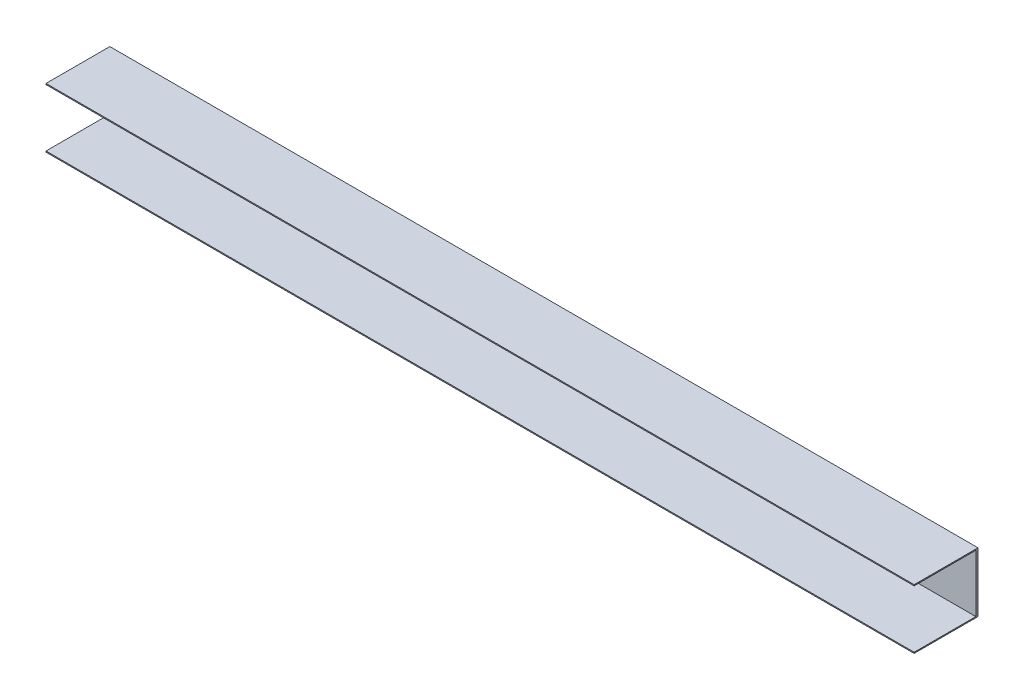
SolidWorks part; units mm, degrees
material "1060 Alloy"
ref_plane "Front Plane" through (0, 0, 0) normal (0, 0, 1) x (1, 0, 0)
ref_plane "Top Plane" through (0, 0, 0) normal (0, 1, 0) x (1, 0, 0)
ref_plane "Right Plane" through (0, 0, 0) normal (1, 0, 0) x (0, 0, -1)
sketch "Sketch1" plane through (0, 0, 0) normal (0, 0, 1) x (1, 0, 0)
  line L1 (-204, 14) -> (204, 14)
  line L2 (-204, 14) -> (-204, -14)
  line L3 (-204, -14) -> (204, -14)
  line L4 (204, 14) -> (204, -14)
  line L5 (-204, 14) -> (204, -14) construction
  line L6 (-204, -14) -> (204, 14) construction
  point P0 (0, 0)
  dimension "D1" = 28
  dimension "D2" = 408
extrude "Boss-Extrude1" add sketch "Sketch1" along normal blind 30
sketch "Sketch2" plane through (0, 0, 30) normal (0, 0, 1) x (1, 0, 0)
  line L1 (213.5, -13.5) -> (-213.5, -13.5)
  line L2 (213.5, -13.5) -> (213.5, 13.5)
  line L3 (213.5, 13.5) -> (-213.5, 13.5)
  line L4 (-213.5, -13.5) -> (-213.5, 13.5)
  line L5 (213.5, -13.5) -> (-213.5, 13.5) construction
  line L6 (213.5, 13.5) -> (-213.5, -13.5) construction
  point P0 (0, 0)
  dimension "D1" = 27
  dimension "D2" = 427
extrude "Cut-Extrude1" cut sketch "Sketch2" against normal blind 29
